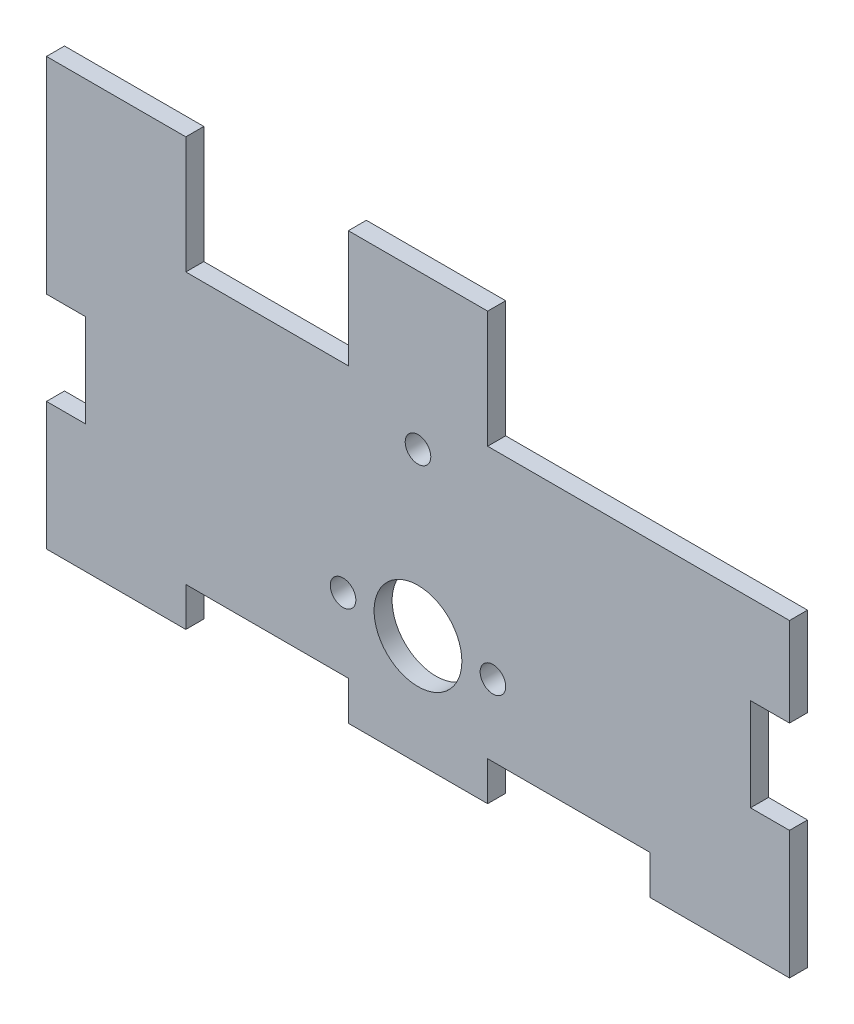
SolidWorks part; units mm, degrees
ref_plane "Front Plane" through (0, 0, 0) normal (0, 0, 1) x (1, 0, 0)
ref_plane "Top Plane" through (0, 0, 0) normal (0, 1, 0) x (1, 0, 0)
ref_plane "Right Plane" through (0, 0, 0) normal (1, 0, 0) x (0, 0, -1)
sketch "Sketch1" plane through (0, 0, 0) normal (0, 0, 1) x (1, 0, 0)
  line L1 (-50.8, 18.5) -> (50.8, 18.5)
  line L2 (-50.8, 18.5) -> (-50.8, -18.5)
  line L3 (-50.8, -18.5) -> (50.8, -18.5)
  line L4 (50.8, 18.5) -> (50.8, -18.5)
  line L5 (-50.8, 18.5) -> (50.8, -18.5) construction
  line L6 (-50.8, -18.5) -> (50.8, 18.5) construction
  point P0 (0, 0)
  dimension "D1" = 37
  dimension "D2" = 101.6
extrude "Boss-Extrude1" add sketch "Sketch1" along normal blind 2.4638
sketch "Sketch2" plane through (0, 0, 2.4638) normal (0, 0, 1) x (1, 0, 0)
  line L0 (0, 0) -> (0, 50000) construction
  line L1 (0, 0) -> (50000, 0) construction
  circle A0 centre (0, -8.73) radius 6
  circle A1 centre (-10.25, -8.73) radius 1.75
  circle A2 centre (0, 13.37) radius 1.75
  circle A3 centre (10.25, -8.73) radius 1.75
  dimension "D1" = 12
  dimension "D4" = 3.5
  dimension "D6" = 3.5
  dimension "D2" = 8.73
  dimension "D3" = 10.25
  dimension "D5" = 22.1
extrude "MotorHoles" cut sketch "Sketch2" against normal through all
sketch "Sketch3" plane through (0, -18.5, 0) normal (0, -1, 0) x (1, 0, 0)
  line L0 (-50.8, 0) -> (50.8, 0) construction
  line L1 (-50.8, 2.4638) -> (-31.75, 2.4638)
  line L2 (-50.8, 2.4638) -> (-50.8, 0)
  line L3 (-50.8, 0) -> (-31.75, 0)
  line L4 (-31.75, 2.4638) -> (-31.75, 0)
  line L5 (0, 0) -> (0, -50000) construction
  line L6 (31.75, 2.4638) -> (31.75, 0)
  line L7 (-9.525, 2.4638) -> (9.525, 2.4638)
  line L8 (-9.525, 2.4638) -> (-9.525, 0)
  line L9 (-9.525, 0) -> (9.525, 0)
  line L10 (9.525, 2.4638) -> (9.525, 0)
  line L11 (-9.525, 2.4638) -> (9.525, 0) construction
  line L12 (-9.525, 0) -> (9.525, 2.4638) construction
  line L13 (50.8, 0) -> (31.75, 0)
  line L14 (50.8, 2.4638) -> (50.8, 0)
  line L15 (50.8, 2.4638) -> (31.75, 2.4638)
  point P10 (0, 1.2319)
  dimension "D1" = 19.05
  dimension "D2" = 19.05
  dimension "D3" = 22.225
extrude "BottomTeeth" add sketch "Sketch3" along normal blind 5.334
sketch "Sketch4" plane through (0, 0, 2.4638) normal (0, 0, 1) x (1, 0, 0)
  line L0 (0, 0) -> (-50000, 0) construction
  line L1 (-50.8, 18.5) -> (-50.8, -23.834) construction
  line L2 (-56.134, 6.35) -> (-45.466, 6.35)
  line L3 (-56.134, 6.35) -> (-56.134, -6.35)
  line L4 (-56.134, -6.35) -> (-45.466, -6.35)
  line L5 (-45.466, 6.35) -> (-45.466, -6.35)
  line L6 (-56.134, 6.35) -> (-45.466, -6.35) construction
  line L7 (-56.134, -6.35) -> (-45.466, 6.35) construction
  line L8 (0, 0) -> (0, -50000) construction
  line L9 (56.134, -6.35) -> (45.466, 6.35) construction
  line L10 (56.134, 6.35) -> (45.466, -6.35) construction
  line L11 (45.466, 6.35) -> (45.466, -6.35)
  line L12 (56.134, -6.35) -> (45.466, -6.35)
  line L13 (56.134, 6.35) -> (56.134, -6.35)
  line L14 (56.134, 6.35) -> (45.466, 6.35)
  point P3 (-50.8, 0)
  point P16 (50.8, 0)
  dimension "D1" = 10.668
  dimension "D2" = 12.7
extrude "Cut-Extrude2" cut sketch "Sketch4" against normal through all
sketch "Sketch5" plane through (0, 18.5, 0) normal (0, 1, 0) x (1, 0, 0)
  line L0 (50.8, -2.4638) -> (-50.8, -2.4638) construction
  line L1 (-50.8, 0) -> (-31.75, 0)
  line L2 (-50.8, 0) -> (-50.8, -2.4638)
  line L3 (-50.8, -2.4638) -> (-31.75, -2.4638)
  line L4 (-31.75, 0) -> (-31.75, -2.4638)
  line L5 (0, 0) -> (0, -50000) construction
  line L7 (-9.525, 0) -> (9.525, 0)
  line L8 (-9.525, 0) -> (-9.525, -2.4638)
  line L9 (-9.525, -2.4638) -> (9.525, -2.4638)
  line L10 (9.525, 0) -> (9.525, -2.4638)
  line L11 (-9.525, 0) -> (9.525, -2.4638) construction
  line L12 (-9.525, -2.4638) -> (9.525, 0) construction
  point P10 (0, -1.2319)
  dimension "D1" = 19.05
  dimension "D2" = 19.05
  dimension "D3" = 22.225
extrude "TopTeeth" add sketch "Sketch5" along normal blind 16.002
